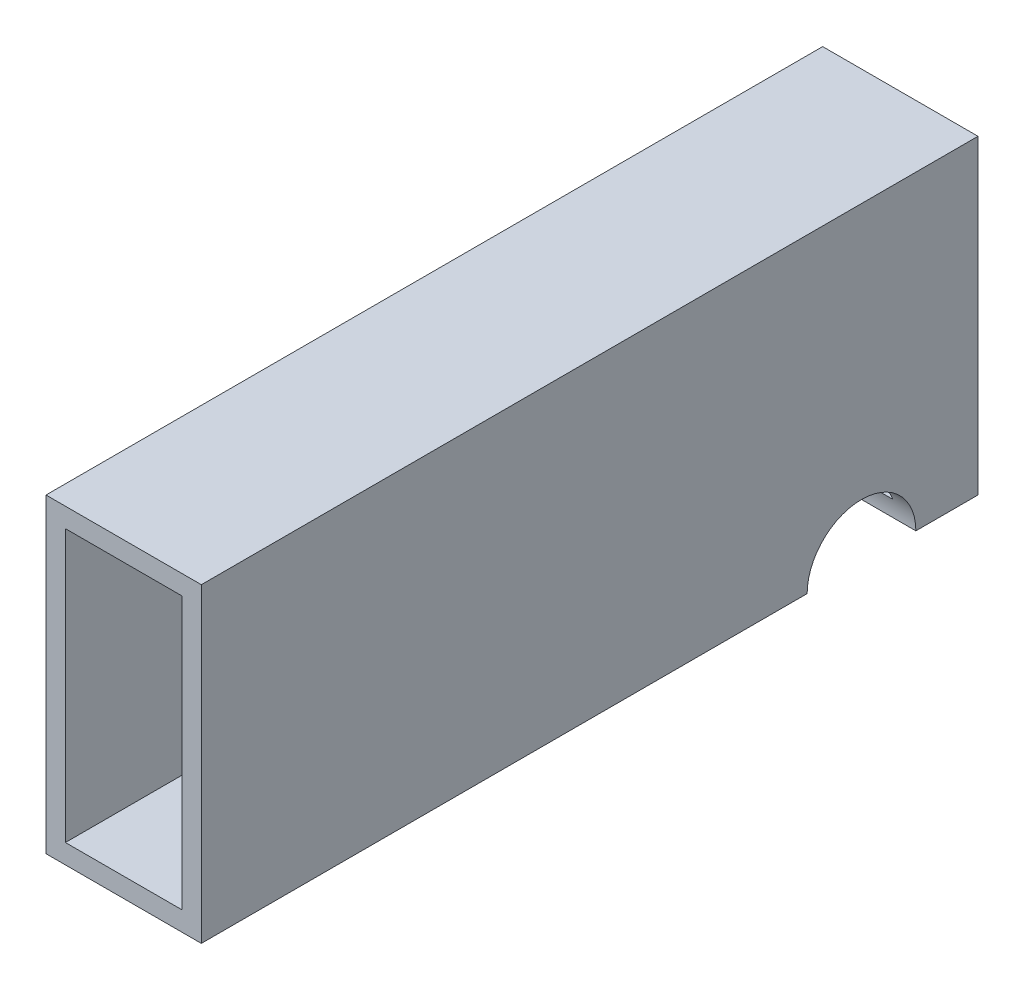
SolidWorks part; units mm, degrees
material "6061-T4 (SS)"
ref_plane "Front Plane" through (0, 0, 0) normal (0, 0, 1) x (1, 0, 0)
ref_plane "Top Plane" through (0, 0, 0) normal (0, 1, 0) x (1, 0, 0)
ref_plane "Right Plane" through (0, 0, 0) normal (1, 0, 0) x (0, 0, -1)
sketch "Sketch1" plane through (0, 0, 0) normal (0, 0, 1) x (1, 0, 0)
  line L0 (-9.525, 22.225) -> (9.525, 22.225)
  line L1 (-12.7, 25.4) -> (12.7, 25.4)
  line L2 (-12.7, 25.4) -> (-12.7, -25.4)
  line L3 (-12.7, -25.4) -> (12.7, -25.4)
  line L4 (12.7, 25.4) -> (12.7, -25.4)
  line L5 (-12.7, 25.4) -> (12.7, -25.4) construction
  line L6 (-12.7, -25.4) -> (12.7, 25.4) construction
  line L7 (9.525, 22.225) -> (9.525, -22.225)
  line L8 (-9.525, -22.225) -> (9.525, -22.225)
  line L9 (-9.525, 22.225) -> (-9.525, -22.225)
  point P0 (0, 0)
  dimension "D1" = 50.8
  dimension "D2" = 25.4
  dimension "D3" = 3.175
extrude "Boss-Extrude1" add sketch "Sketch1" along normal mid plane 127
sketch "Sketch2" plane through (12.7, 0, 0) normal (1, 0, 0) x (0, 0, -1)
  line L0 (63.5, -25.4) -> (63.5, 25.4) construction
  line L1 (-63.5, -25.4) -> (63.5, -25.4) construction
  circle A0 centre (44.45, -25.4) radius 8.89
  dimension "D1" = 19.05
  dimension "D2" = 17.78
extrude "Cut-Extrude1" cut sketch "Sketch2" against normal through all
